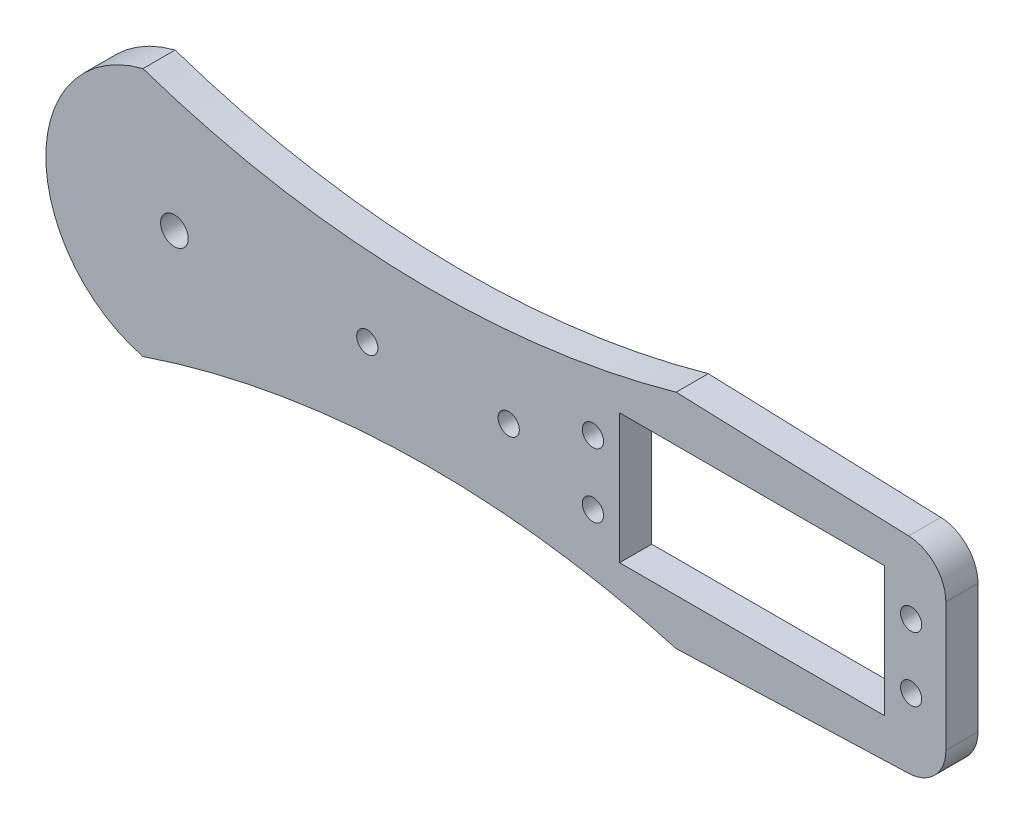
SolidWorks part; units mm, degrees
ref_plane "Спереди" through (0, 0, 0) normal (0, 0, 1) x (1, 0, 0)
ref_plane "Сверху" through (0, 0, 0) normal (0, 1, 0) x (1, 0, 0)
ref_plane "Справа" through (0, 0, 0) normal (1, 0, 0) x (0, 0, -1)
other "Configuration Table"
sketch "Eskiz_kontur" plane through (0, 0, 0) normal (0, 0, 1) x (1, 0, 0)
  line L0 (78.0435, 17.2681) -> (114.2094, 15.9963)
  line L1 (120, 10) -> (120, -10)
  line L2 (114.2094, -15.9963) -> (78.0435, -17.2681)
  line L3 (69.25, 10.1) -> (69.25, -10.1)
  line L4 (69.25, -10.1) -> (110.45, -10.1)
  line L5 (110.45, 10.1) -> (69.25, 10.1)
  line L6 (110.45, -10.1) -> (110.45, 10.1)
  arc A0 (78.0435, -17.2681) -> (-4.8917, -19.3926) centre (40, -152) ccw
  arc A1 (-4.8917, -19.3926) -> (-4.8917, 19.3926) centre (0, 0) cw
  arc A2 (-4.8917, 19.3926) -> (78.0435, 17.2681) centre (40, 152) ccw
  arc A3 (114.2094, 15.9963) -> (120, 10) centre (114, 10) cw
  arc A4 (120, -10) -> (114.2094, -15.9963) centre (114, -10) cw
extrude "Plastina" add sketch "Eskiz_kontur" along normal blind 5
sketch "Eskiz_otverstiya" plane through (0, 0, 0) normal (0, 0, 1) x (1, 0, 0)
  circle A0 centre (65.1, -5) radius 1.65
  circle A1 centre (114.6, -5) radius 1.65
  circle A2 centre (0, 0) radius 2.15
  circle A3 centre (30, 0) radius 1.65
  circle A4 centre (52, 0) radius 1.65
  circle A5 centre (65.1, 5) radius 1.65
  circle A6 centre (114.6, 5) radius 1.65
  dimension "d1" = 3.3
  dimension "d2" = 3.3
  dimension "d3" = 4.3
  dimension "d4" = 3.3
  dimension "d5" = 3.3
  dimension "d6" = 3.3
  dimension "d7" = 3.3
extrude "Otverstiya" cut sketch "Eskiz_otverstiya" against normal through all and the other way through all
equation "\"T3\" = 3"
equation "\"T5\" = 5"
equation "\"D_M3\" = 3.3"
equation "\"D_M2\" = 2.2"
equation "\"D_M3_TAP\" = 2.5"
equation "\"D_M4\" = 4.5"
equation "\"L1\" = 100"
equation "\"L2\" = 100"
equation "\"D1@Plastina\" = \"T5\""
equation "\"d1@Eskiz_otverstiya\" = \"D_M3\""
equation "\"d2@Eskiz_otverstiya\" = \"D_M3\""
equation "\"d4@Eskiz_otverstiya\" = \"D_M3\""
equation "\"d5@Eskiz_otverstiya\" = \"D_M3\""
equation "\"d6@Eskiz_otverstiya\" = \"D_M3\""
equation "\"d7@Eskiz_otverstiya\" = \"D_M3\""
